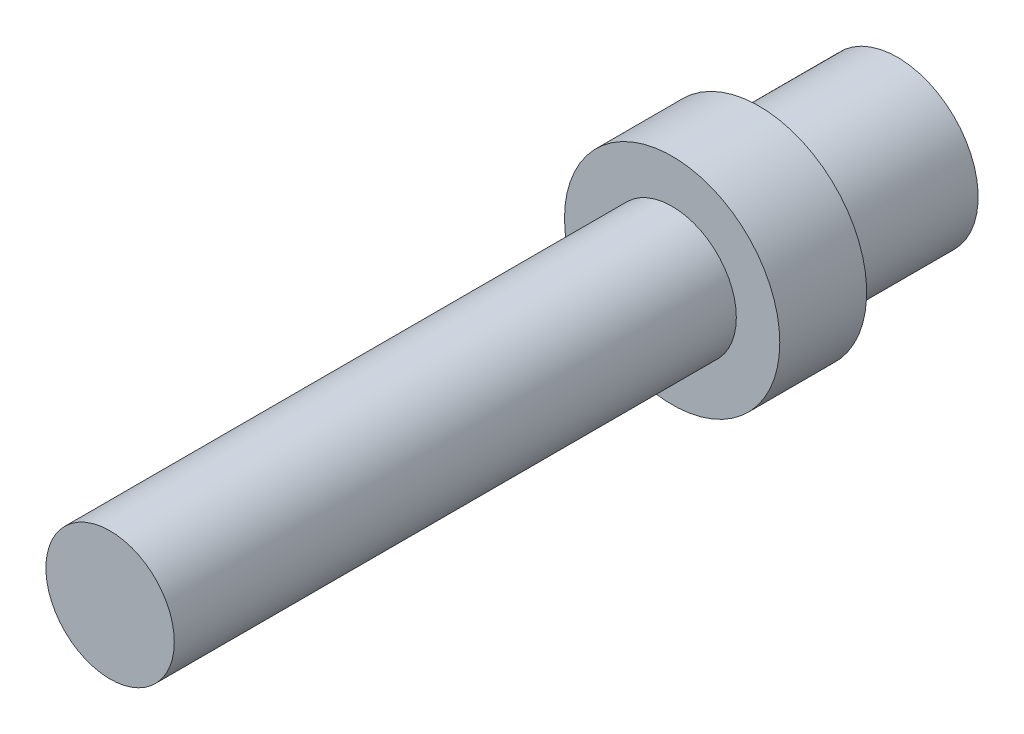
SolidWorks part; units mm, degrees
ref_plane "Alzado" through (0, 0, 0) normal (0, 0, 1) x (1, 0, 0)
ref_plane "Planta" through (0, 0, 0) normal (0, 1, 0) x (1, 0, 0)
ref_plane "Vista lateral" through (0, 0, 0) normal (1, 0, 0) x (0, 0, -1)
sketch "Croquis1" plane through (0, 0, 0) normal (0, 0, 1) x (1, 0, 0)
  circle A0 centre (0, 0) radius 14
  dimension "D1" = 28
extrude "Saliente-Extruir1" add sketch "Croquis1" along normal blind 85
sketch "Croquis2" plane through (0, 0, 0) normal (0, 0, -1) x (-1, 0, 0)
  circle A0 centre (0, 0) radius 10.65
  dimension "D1" = 21.3
extrude "Cortar-Extruir2" cut sketch "Croquis2" against normal blind 18 flip side to cut
sketch "Croquis5" plane through (0, 0, 85) normal (0, 0, 1) x (1, 0, 0)
  circle A0 centre (0, 0) radius 14
extrude "Cortar-Extruir3" cut sketch "Croquis5" against normal blind 55.7
sketch "Croquis6" plane through (0, 0, 29.3) normal (0, 0, 1) x (1, 0, 0)
  circle A0 centre (0, 0) radius 8.35
  dimension "D1" = 16.7
extrude "Saliente-Extruir2" add sketch "Croquis6" along normal blind 73.1
sketch "Croquis7" plane through (0, 0, 0) normal (0, 0, -1) x (-1, 0, 0)
  circle A0 centre (0, 0) radius 10.5
  dimension "D1" = 21
extrude "Cortar-Extruir5" cut sketch "Croquis7" against normal blind 18 flip side to cut
